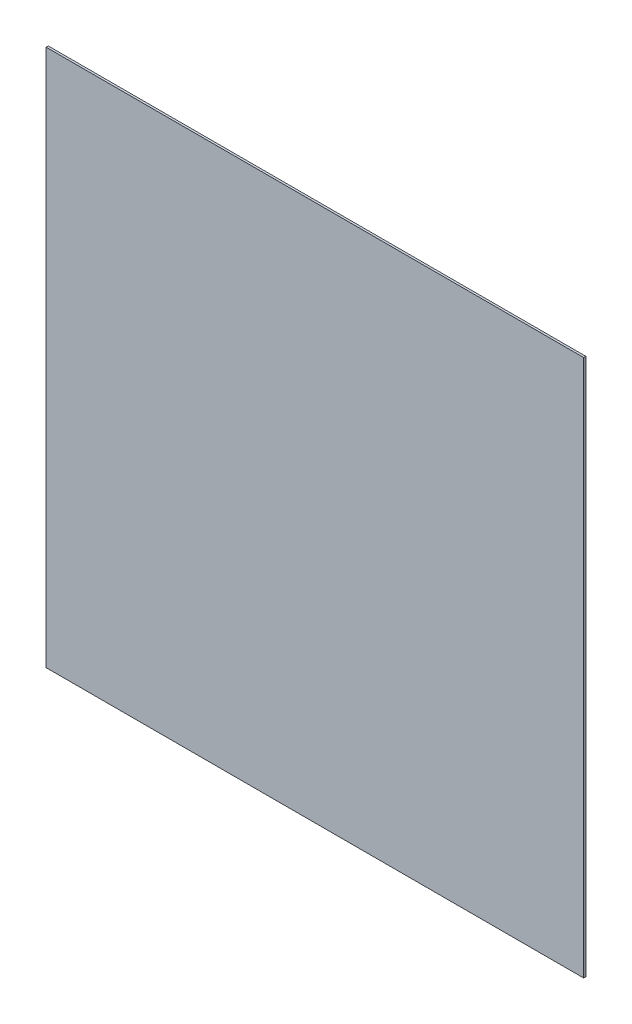
SolidWorks part; units mm, degrees
material "Glas"
ref_plane "Ebene vorne" through (0, 0, 0) normal (0, 0, 1) x (1, 0, 0)
ref_plane "Ebene oben" through (0, 0, 0) normal (0, 1, 0) x (1, 0, 0)
ref_plane "Ebene rechts" through (0, 0, 0) normal (1, 0, 0) x (0, 0, -1)
sketch "Skizze1" plane through (0, 0, 0) normal (0, 0, 1) x (1, 0, 0)
  line L1 (500, 4) -> (-500, 4)
  line L2 (500, 4) -> (500, -996)
  line L3 (500, -996) -> (-500, -996)
  line L4 (-500, 4) -> (-500, -996)
extrude "Aufsatz-Linear austragen1" add sketch "Skizze1" along normal blind 4
equation "\"wall_thickness\"= 4mm"
equation "\"wall_height\"= 300"
equation "\"D1@Aufsatz-Linear austragen1\"=\"wall_thickness\""
